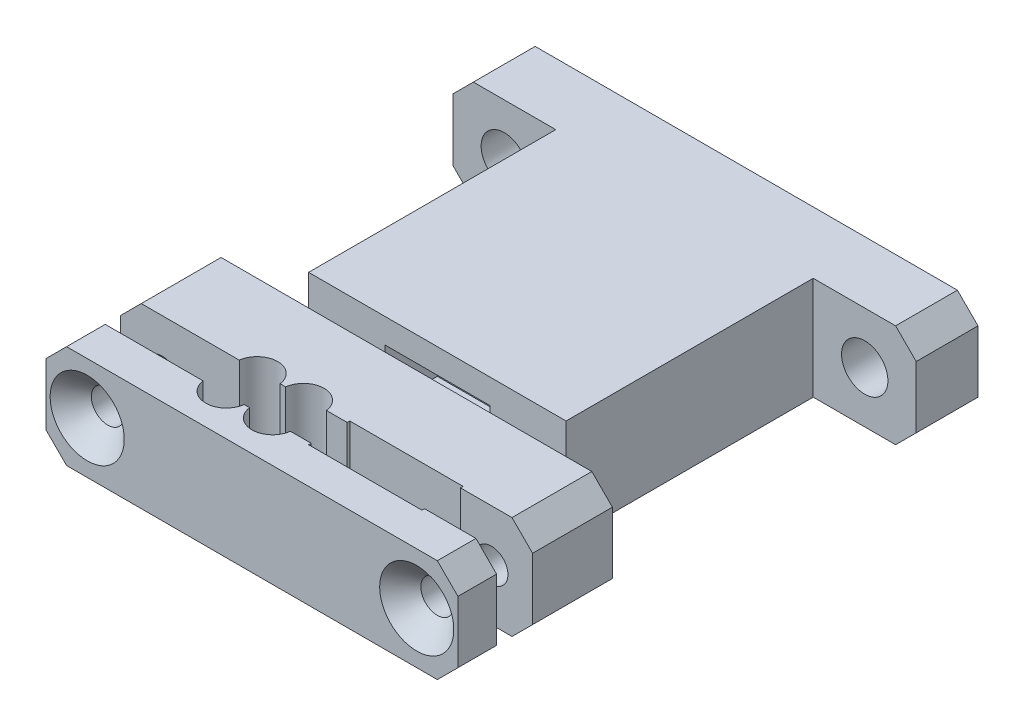
SolidWorks part; units mm, degrees
material "3D printed plastic"
ref_plane "Front Plane" through (0, 0, 0) normal (0, 0, 1) x (1, 0, 0)
ref_plane "Top Plane" through (0, 0, 0) normal (0, 1, 0) x (1, 0, 0)
ref_plane "Right Plane" through (0, 0, 0) normal (1, 0, 0) x (0, 0, -1)
sketch "Sketch3" plane through (0, 0, 0) normal (0, 1, 0) x (1, 0, 0)
  line L0 (-12.5, -30) -> (12.5, -30)
  line L1 (22.5, 0) -> (-22.5, 0)
  line L2 (12.5, -6) -> (12.5, -30)
  line L3 (-12.5, -6) -> (-22.5, -6)
  line L4 (12.5, -6) -> (22.5, -6)
  line L5 (22.5, -6) -> (22.5, 0)
  line L6 (-22.5, -6) -> (-22.5, 0)
  line L7 (-6.5, -39) -> (-2, -39) construction
  line L8 (-12.5, -6) -> (-12.5, -30)
  line L9 (-20, -31) -> (20, -31)
  line L10 (-20, -31) -> (-20, -43)
  line L11 (-20, -43) -> (20, -43)
  line L12 (20, -31) -> (20, -43)
  line L13 (2, -38.5) -> (13, -38.5)
  line L14 (2, -38.5) -> (2, -39.5)
  line L15 (2, -39.5) -> (13, -39.5)
  line L16 (13, -38.5) -> (13, -39.5)
  line L17 (-2, -39) -> (2, -39) construction
  line L18 (0, -31) -> (0, -39) construction
  line L19 (0, -30) -> (0, -31) construction
  circle A0 centre (-6.5, -39) radius 2
  circle A1 centre (-2, -39) radius 2
  dimension "D5" = 4
  dimension "D13" = 4
  dimension "D1" = 30
  dimension "D2" = 25
  dimension "D3" = 6
  dimension "D4" = 45
  dimension "D6" = 4.5
  dimension "D7" = 1
  dimension "D8" = 11
  dimension "D9" = 1
  dimension "D10" = 40
  dimension "D11" = 4
  dimension "D12" = 8
extrude "Boss-Extrude2" add sketch "Sketch3" along normal mid plane 10
sketch "Sketch4" plane through (0, 0, 6) normal (0, 0, 1) x (1, 0, 0)
  line L0 (-17.5, 0) -> (17.5, 0) construction
  circle A0 centre (17.5, 0) radius 2.25
  circle A1 centre (-17.5, 0) radius 2.25
  dimension "D1" = 35
  dimension "D2" = 4.5
extrude "Cut-Extrude1" cut sketch "Sketch4" against normal through all
sketch "Sketch5" plane through (0, 0, 30) normal (0, 0, 1) x (1, 0, 0)
  line L0 (9, 0) -> (-9, 0) construction
  circle A0 centre (-9, 0) radius 1.5
  circle A1 centre (9, 0) radius 1.5
  dimension "D1" = 3
  dimension "D2" = 18
extrude "Cut-Extrude2" cut sketch "Sketch5" against normal blind 12 and the other way blind 5
sketch "Sketch6" plane through (0, 0, 30) normal (0, 0, 1) x (1, 0, 0)
  line L0 (-5.1, 2.6) -> (5.1, -2.6) construction
  line L1 (-5.1, 2.6) -> (5.1, 2.6)
  line L2 (-5.1, 2.6) -> (-5.1, -2.6)
  line L3 (-5.1, -2.6) -> (5.1, -2.6)
  line L4 (5.1, 2.6) -> (5.1, -2.6)
  dimension "D1" = 10.2
  dimension "D2" = 5.2
extrude "Cut-Extrude3" cut sketch "Sketch6" against normal blind 5.1
sketch "Sketch7" plane through (0, 5, 0) normal (0, 1, 0) x (1, 0, 0)
  line L0 (-20, -39) -> (20, -39)
  line L1 (-20, -31) -> (-20, -43) construction
  line L2 (20, -43) -> (20, -31) construction
  line L3 (-2, -39) -> (-2, -35.0756) construction
  circle A0 centre (-2, -39) radius 2 construction
extrude "Cut-Extrude-Thin3" cut sketch "Sketch7" against normal through all thin thin type mid plane wall 0.5
sketch "Sketch9" plane through (0, 0, 31) normal (0, 0, -1) x (-1, 0, 0)
  line L0 (-5.1, 2.6) -> (5.1, 2.6) construction
  line L1 (5.1, 2.6) -> (-5.1, 2.6)
  line L2 (5.1, 2.6) -> (5.1, -2.6)
  line L3 (5.1, -2.6) -> (-5.1, -2.6)
  line L4 (-5.1, 2.6) -> (-5.1, -2.6)
  line L5 (5.1, -2.6) -> (-5.1, -2.6) construction
  line L6 (-5.1, -2.6) -> (-5.1, 2.6) construction
  line L7 (-5.1, -2.6) -> (-5.1, 2.6) construction
  line L8 (5.1, 2.6) -> (5.1, -2.6) construction
  line L9 (5.1, 2.6) -> (5.1, -2.6) construction
extrude "Cut-Extrude4" cut sketch "Sketch9" against normal blind 5.1
move or copy body "Body-Move/Copy1" bodies to move or copy 110 109 copy no translate (0, 0, -1)
sketch "Sketch10" plane through (0, 0, 42) normal (0, 0, 1) x (1, 0, 0)
  line L0 (16, 0) -> (-16, 0) construction
  line L1 (20, 5) -> (20, -5) construction
  circle A0 centre (-16, 0) radius 1.6
  circle A1 centre (16, 0) radius 1.6
  dimension "D1" = 4
  dimension "D2" = 3.2
extrude "Cut-Extrude5" cut sketch "Sketch10" against normal up to surface (12 mm away)
sketch "Sketch11" plane through (0, 0, 30) normal (0, 0, -1) x (-1, 0, 0)
  line L1 (16, -3.2909) -> (18.85, -1.6454)
  line L2 (18.85, -1.6454) -> (18.85, 1.6454)
  line L3 (18.85, 1.6454) -> (16, 3.2909)
  line L4 (16, 3.2909) -> (13.15, 1.6454)
  line L5 (13.15, 1.6454) -> (13.15, -1.6454)
  line L6 (13.15, -1.6454) -> (16, -3.2909)
  line L7 (-16, -3.2909) -> (-13.15, -1.6454)
  line L8 (-13.15, -1.6454) -> (-13.15, 1.6454)
  line L9 (-13.15, 1.6454) -> (-16, 3.2909)
  line L10 (-16, 3.2909) -> (-18.85, 1.6454)
  line L11 (-18.85, 1.6454) -> (-18.85, -1.6454)
  line L12 (-18.85, -1.6454) -> (-16, -3.2909)
  circle A0 centre (16, 0) radius 2.85 construction
  circle A1 centre (-16, 0) radius 2.85 construction
  dimension "D1" = 5.7
extrude "Cut-Extrude6" cut sketch "Sketch11" against normal blind 3
chamfer "Chamfer1" distance 2 angle 45 2 edges at (17.6, 0, 42) (-14.4, 0, 42)
sketch "Sketch12" plane through (0, 0, 42) normal (0, 0, 1) x (1, 0, 0)
  line L0 (-20, 5) -> (-20, 3)
  line L1 (-20, 3) -> (-18, 5)
  line L2 (-22.5, 5) -> (-12.5, 5) construction
  line L3 (-18, 5) -> (-20, 5)
  line L4 (0, 0) -> (-24.6462, 0) construction
  line L5 (-18, -5) -> (-20, -5)
  line L6 (-20, -3) -> (-18, -5)
  line L7 (-20, -5) -> (-20, -3)
  line L8 (0, 0) -> (0, 6.4221) construction
  line L9 (20, -5) -> (20, -3)
  line L10 (20, -3) -> (18, -5)
  line L11 (18, -5) -> (20, -5)
  line L12 (18, 5) -> (20, 5)
  line L13 (20, 3) -> (18, 5)
  line L14 (20, 5) -> (20, 3)
  dimension "D1" = 2
extrude "Cut-Extrude7" cut sketch "Sketch12" against normal up to surface (12 mm away)
chamfer "Chamfer2" distance 2 angle 45 4 edges at (22.5, -5, 3) (22.5, 5, 3) (-22.5, -5, 3) (-22.5, 5, 3)
move or copy body "Body-Move/Copy2" bodies to move or copy 117 copy no translate (0, 0, 3)
move or copy body "Body-Move/Copy3" bodies to move or copy 116 copy no translate (0, 0, 6)
